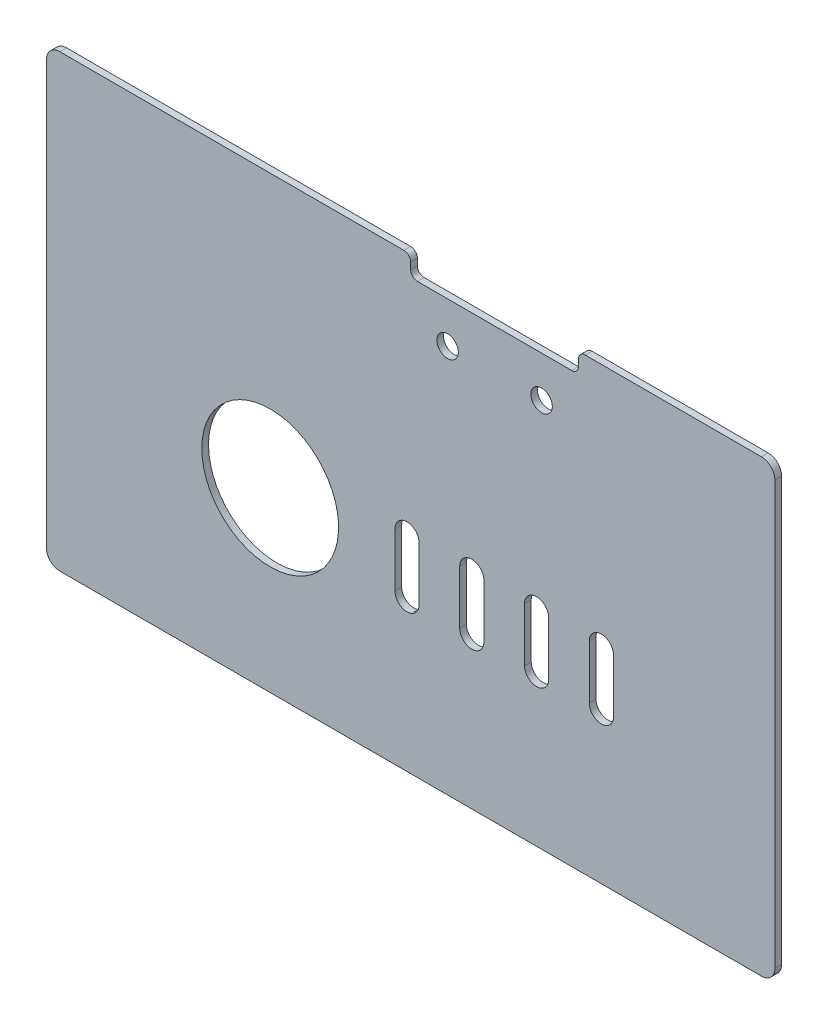
SolidWorks part; units mm, degrees
material "Thornel Mat VMA"
ref_plane "前视基准面" through (0, 0, 0) normal (0, 0, 1) x (1, 0, 0)
ref_plane "上视基准面" through (0, 0, 0) normal (0, 1, 0) x (1, 0, 0)
ref_plane "右视基准面" through (0, 0, 0) normal (1, 0, 0) x (0, 0, -1)
other "Configuration Table"
sketch "草图1" plane through (0, 0, 0) normal (0, 0, 1) x (1, 0, 0)
  line L0 (0, 0) -> (0, -50000) construction
  line L1 (-63.75, -35) -> (63.75, -35)
  line L2 (-63.75, -35) -> (-63.75, 35)
  line L3 (-63.75, 35) -> (63.75, 35)
  line L4 (63.75, -35) -> (63.75, 35)
  line L5 (-63.75, -35) -> (63.75, 35) construction
  line L6 (-63.75, 35) -> (63.75, -35) construction
  line L7 (-7, 22.9) -> (7, 22.9) construction
  circle A0 centre (-7, 22.9) radius 1.6
  circle A1 centre (7, 22.9) radius 1.6
  point P0 (0, 0)
  point P11 (0, 22.9)
  dimension "D4" = 3.2
  dimension "D1" = 70
  dimension "D2" = 127.5
  dimension "D3" = 12.1
  dimension "D5" = 14
extrude "凸台-拉伸1" add sketch "草图1" along normal blind 1
sketch "草图2" plane through (0, 0, 1) normal (0, 0, 1) x (1, 0, 0)
  line L0 (63.75, -35) -> (63.75, 35) construction
  line L1 (-63.75, 35) -> (63.75, 35)
  line L2 (-63.75, 35) -> (-63.75, 32)
  line L3 (-63.75, 32) -> (63.75, 32)
  line L4 (63.75, 35) -> (63.75, 32)
  dimension "D1" = 3
extrude "切除-拉伸1" cut sketch "草图2" against normal blind 10
sketch "草图3" plane through (0, 0, 1) normal (0, 0, 1) x (1, 0, 0)
  line L0 (-63.75, -35) -> (63.75, -35) construction
  line L1 (63.75, 32) -> (41.75, 32)
  line L2 (63.75, 32) -> (63.75, -35)
  line L3 (63.75, -35) -> (41.75, -35)
  line L4 (41.75, 32) -> (41.75, -35)
  dimension "D1" = 22
extrude "切除-拉伸2" cut sketch "草图3" against normal blind 10
sketch "草图4" plane through (0, 0, 1) normal (0, 0, 1) x (1, 0, 0)
  line L1 (-63.75, 32) -> (-66.75, 32)
  line L2 (-63.75, 32) -> (-63.75, -35)
  line L3 (-63.75, -35) -> (-66.75, -35)
  line L4 (-66.75, 32) -> (-66.75, -35)
  dimension "D1" = 3
extrude "凸台-拉伸3" add sketch "草图4" against normal blind 1
sketch "草图5" plane through (0, 0, 1) normal (0, 0, 1) x (1, 0, 0)
  line L0 (-11.24, -12.5908) -> (-11.2398, -4.59)
  line L1 (-14.8387, -4.5893) -> (-14.8391, -12.59)
  line L2 (-1.5906, -12.59) -> (-1.5906, -4.59)
  line L3 (-5.1906, -4.59) -> (-5.1906, -12.59)
  line L4 (8.0594, -12.59) -> (8.0594, -4.59)
  line L5 (4.4594, -4.59) -> (4.4594, -12.59)
  line L6 (17.7094, -12.59) -> (17.7094, -4.59)
  line L7 (14.1094, -4.59) -> (14.1094, -12.59)
  line L8 (16.7094, -12.59) -> (16.7094, -4.59) construction
  line L9 (15.1094, -4.59) -> (15.1094, -12.59) construction
  line L10 (7.0594, -12.59) -> (7.0594, -4.59) construction
  line L11 (5.4594, -4.59) -> (5.4594, -12.59) construction
  line L12 (-2.5906, -12.59) -> (-2.5906, -4.59) construction
  line L13 (-4.1906, -4.59) -> (-4.1906, -12.59) construction
  line L14 (-12.24, -12.59) -> (-12.2398, -4.59) construction
  line L15 (-13.8387, -4.59) -> (-13.8391, -12.59) construction
  line L16 (41.75, 32) -> (41.75, -35) construction
  line L17 (-66.75, -35) -> (41.75, -35) construction
  arc A0 (-1.5906, -4.59) -> (-5.1906, -4.59) centre (-3.3906, -4.59) ccw
  arc A1 (-5.1906, -12.59) -> (-1.5906, -12.59) centre (-3.3906, -12.59) ccw
  arc A2 (8.0594, -4.59) -> (4.4594, -4.59) centre (6.2594, -4.59) ccw
  arc A3 (4.4594, -12.59) -> (8.0594, -12.59) centre (6.2594, -12.59) ccw
  arc A4 (14.1094, -12.59) -> (17.7094, -12.59) centre (15.9094, -12.59) ccw
  arc A5 (17.7094, -4.59) -> (14.1094, -4.59) centre (15.9094, -4.59) ccw
  arc A6 (15.1094, -12.59) -> (16.7094, -12.59) centre (15.9094, -12.59) ccw construction
  arc A7 (16.7094, -4.59) -> (15.1094, -4.59) centre (15.9094, -4.59) ccw construction
  arc A8 (7.0594, -4.59) -> (5.4594, -4.59) centre (6.2594, -4.59) ccw construction
  arc A9 (5.4594, -12.59) -> (7.0594, -12.59) centre (6.2594, -12.59) ccw construction
  arc A10 (-2.5906, -4.59) -> (-4.1906, -4.59) centre (-3.3906, -4.59) ccw construction
  arc A11 (-4.1906, -12.59) -> (-2.5906, -12.59) centre (-3.3906, -12.59) ccw construction
  spline S0 degree 1 poles (-11.2398, -4.59) (-14.8387, -4.5893) knots 0 0 1 1 construction
  spline S1 degree 1 poles (-14.8391, -12.59) (-11.24, -12.5908) knots 0 0 1 1 construction
  spline S2 degree 3 poles (-11.2398, -4.59) (-11.2397, -4.1312) (-11.6284, -3.1752) (-13.0377, -2.5987) (-14.4481, -3.1736) (-14.8383, -4.1301) (-14.8387, -4.5893) knots 0.000124 0.000124 0.000124 0.000124 0.250093 0.500062 0.750031 1 1 1 1
  spline S3 degree 3 poles (-12.2398, -4.59) (-12.2397, -4.381) (-12.3256, -4.1731) (-12.6211, -3.877) (-12.829, -3.7907) (-13.2476, -3.7904) (-13.4557, -3.8764) (-13.7521, -4.1724) (-13.8385, -4.3805) (-13.8387, -4.59) knots 0 0 0 0 0.25 0.25 0.5 0.5 0.75 0.75 1 1 1 1 construction
  spline S4 degree 3 poles (-13.8391, -12.59) (-13.8391, -12.7989) (-13.7531, -13.0067) (-13.4575, -13.3025) (-13.2498, -13.3887) (-12.8314, -13.3891) (-12.6233, -13.3032) (-12.3269, -13.0075) (-12.2403, -12.7995) (-12.24, -12.59) knots 0 0 0 0 0.25 0.25 0.5 0.5 0.75 0.75 1 1 1 1 construction
  spline S5 degree 3 poles (-23.2392, -8.3092) (-23.8207, 12.0524) (-44.1823, 11.4708) (-43.6008, -8.8908) (-43.0193, -29.2524) (-22.6577, -28.6708) (-23.2392, -8.3092) (-23.8207, 12.0524) (-44.1823, 11.4708) knots -0.5 0 0 0 0.5 0.5 0.5 1 1 1 1.5 1.5 1.5 weights 1 0.333333 0.333333 1 0.333333 0.333333 1 0.333333 0.333333 only from (-23.2392, -8.3092) to (-23.2392, -8.3092)
  spline S6 degree 3 poles (-14.8391, -12.59) (-14.8391, -13.0488) (-14.4501, -14.0046) (-13.0407, -14.5809) (-11.6301, -14.0052) (-11.2408, -13.0497) (-11.24, -12.5908) knots -0.000006 -0.000006 -0.000006 -0.000006 0.250075 0.500157 0.750239 1.00032 1.00032 1.00032 1.00032
  dimension "D1" = 0.8
  dimension "D2" = 25.8406
  dimension "D3" = 35.4906
  dimension "D4" = 45.1406
  dimension "D5" = 53.9898
  dimension "D6" = 53.99
  dimension "D7" = 55.5887
  dimension "D8" = 55.5891
  dimension "D9" = 64.9892
  dimension "D10" = 22.41
  dimension "D11" = 1
  dimension "D12" = 26.6908
  dimension "D15" = 30.41
extrude "切除-拉伸3" cut sketch "草图5" against normal mid plane 10
fillet "圆角1" radius 2 4 edges at (41.75, 32, 0.5) (-66.75, -35, 0.5) (41.75, -35, 0.5) (-66.75, 32, 0.5)
sketch "草图6" plane through (0, 0, 1) normal (0, 0, 1) x (1, 0, 0)
  line L0 (-7, 22.9) -> (7, 22.9) construction
  line L1 (-64.75, 32) -> (39.75, 32) construction
  line L2 (-12.5, 29) -> (12.5, 29)
  line L3 (-12.5, 29) -> (-12.5, 35)
  line L4 (-12.5, 35) -> (12.5, 35)
  line L5 (12.5, 29) -> (12.5, 35)
  line L6 (-12.5, 29) -> (12.5, 35) construction
  line L7 (-12.5, 35) -> (12.5, 29) construction
  line L8 (0, 32) -> (0, 22.9) construction
  point P4 (0, 32)
  dimension "D1" = 25
  dimension "D2" = 6
extrude "切除-拉伸4" cut sketch "草图6" against normal blind 10
fillet "圆角2" radius 1 4 edges at (12.5, 29, 0.5) (-12.5, 29, 0.5) (-12.5, 32, 0.5) (12.5, 32, 0.5)
